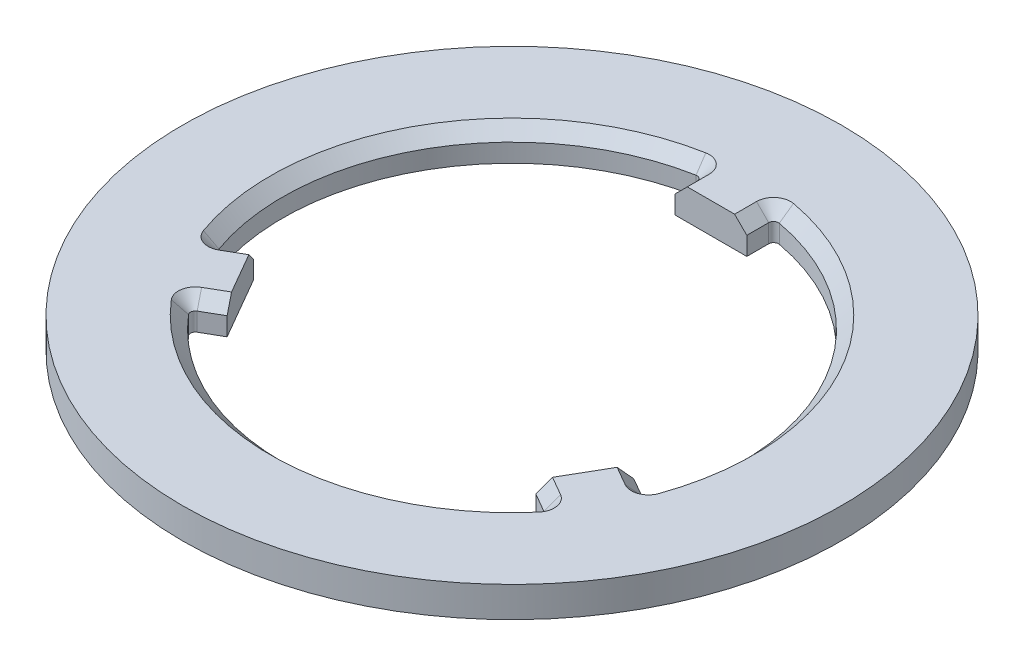
SolidWorks part; units mm, degrees
material "1.0037 (S235JR)"
ref_plane "Front Plane" through (0, 0, 0) normal (0, 0, 1) x (1, 0, 0)
ref_plane "Top Plane" through (0, 0, 0) normal (0, 1, 0) x (1, 0, 0)
ref_plane "Right Plane" through (0, 0, 0) normal (1, 0, 0) x (0, 0, -1)
sketch "Sketch1" plane through (0, 0, 0) normal (0, 1, 0) x (1, 0, 0)
  circle A0 centre (0, 0) radius 54
  circle A1 centre (0, 0) radius 37.6
  dimension "D1" = 108
  dimension "D2" = 75.2
extrude "Boss-Extrude1" add sketch "Sketch1" along normal mid plane 5
sketch "Sketch2" plane through (0, 0, 0) normal (0, 1, 0) x (1, 0, 0)
  line L0 (0, -1000) -> (0, 49000) construction
  line L1 (-5.875, 32.6) -> (5.875, 32.6)
  line L2 (5.875, 32.6) -> (5.875, 37.1382)
  line L3 (-5.875, 32.6) -> (-5.875, 37.1382)
  circle A0 centre (0, 0) radius 37.6 construction
  arc A1 (5.875, 37.1382) -> (-5.875, 37.1382) centre (0, 0) ccw
  point P5 (0, 32.6)
  dimension "D1" = 11.75
  dimension "D2" = 32.6
extrude "Boss-Extrude2" add sketch "Sketch2" along normal mid plane 5
fillet "Fillet1" radius 0.8 2 edges at (5.875, 0, -37.1382) (-5.875, 0, -37.1382)
pattern_circular "CirPattern1" count 3 over 360 about axis through (0, 0, 0) along (0, 1, 0) of "Boss-Extrude2", "Fillet1"
chamfer "Chamfer2" distance 2 angle 45 15 edges at (5.875, 2.5, -34.3948) (-32.5626, 2.5, -18.8) (-5.875, 2.5, -34.3948) (6.1632, 2.5, -36.8044) (-6.1632, 2.5, -36.8044) (26.8493, 2.5, 22.2853) (-32.7243, 2.5, 12.1095) (32.7243, 2.5, 12.1095) (32.5626, 2.5, -18.8) (28.792, 2.5, 23.7397) (34.9551, 2.5, 13.0647) (-26.8493, 2.5, 22.2853) (0, 2.5, 37.6) (-34.9551, 2.5, 13.0647) (-28.792, 2.5, 23.7397)
